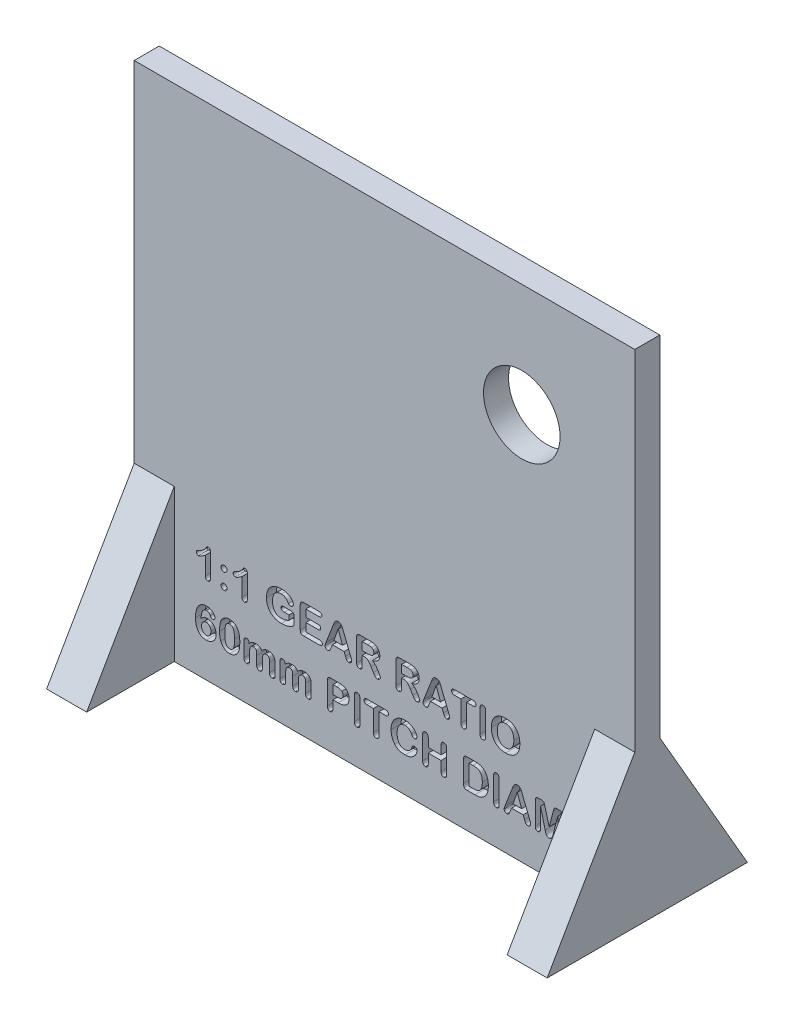
SolidWorks part; units mm, degrees
ref_plane "Front Plane" through (0, 0, 0) normal (0, 0, 1) x (1, 0, 0)
ref_plane "Top Plane" through (0, 0, 0) normal (0, 1, 0) x (1, 0, 0)
ref_plane "Right Plane" through (0, 0, 0) normal (1, 0, 0) x (0, 0, -1)
sketch "Sketch1" plane through (0, 0, 0) normal (0, 0, 1) x (1, 0, 0)
  line L0 (0, 0) -> (42.4264, 42.4264)
  line L1 (-35, -35) -> (65, -35)
  line L2 (-35, -35) -> (-35, 65)
  line L3 (-35, 65) -> (65, 65)
  line L4 (65, -35) -> (65, 65)
  line L5 (0, 0) -> (30, 0)
  line L7 (22.0644, -35) -> (-22.0644, -35)
  circle A0 centre (42.4264, 42.4264) radius 30
  circle A1 centre (0, 0) radius 30
  circle A4 centre (42.4264, 42.4264) radius 7.65
  point P12 (15, 0)
  point P13 (15, 65)
  dimension "D3" = 60
  dimension "D4" = 60
  dimension "D6" = 35
  dimension "D7" = 15.3
  dimension "D1" = 100
  dimension "D2" = 100
  dimension "D5" = 45
  dimension "D8" = 35
extrude "Boss-Extrude1" add sketch "Sketch1" along normal blind 5
sketch "Sketch3" plane through (65, 0, 0) normal (1, 0, 0) x (0, 0, -1)
  line L0 (-2.5, -0.359) -> (-22.5, -35)
  line L1 (-22.5, -35) -> (17.5, -35)
  line L2 (17.5, -35) -> (-2.5, -0.359)
  line L3 (-5, -35) -> (0, -35) construction
  point P6 (-2.5, -35)
  dimension "D1" = 40
  dimension "D2" = 60
  dimension "D3" = 60
extrude "Boss-Extrude3" add sketch "Sketch3" against normal blind 8
sketch "Sketch4" plane through (-35, 0, 0) normal (-1, 0, 0) x (0, 0, 1)
  line L0 (2.5, -35) -> (2.5, -0.359)
  line L1 (5, -35) -> (0, -35) construction
  line L2 (2.5, -0.359) -> (22.5, -35)
  line L3 (22.5, -35) -> (2.5, -35)
  dimension "D1" = 60
  dimension "D2" = 20
extrude "Boss-Extrude4" add sketch "Sketch4" against normal blind 8
sketch "Sketch5" plane through (0, 0, 0) normal (0, 0, -1) x (-1, 0, 0)
  circle A1 centre (0, 0) radius 7.35
  dimension "D2" = 14.7
extrude "Boss-Extrude5" add sketch "Sketch5" along normal blind 15.5
sketch "Sketch6" plane through (0, 0, 5) normal (0, 0, 1) x (1, 0, 0)
  text T0 "1:1 GEAR RATIO\r\n60mm PITCH DIAM.\r\n" font "Arial Rounded MT Bold" height 6
  point P4 (-24.2965, 0)
extrude "Cut-Extrude1" cut sketch "Sketch6" against normal blind 2
